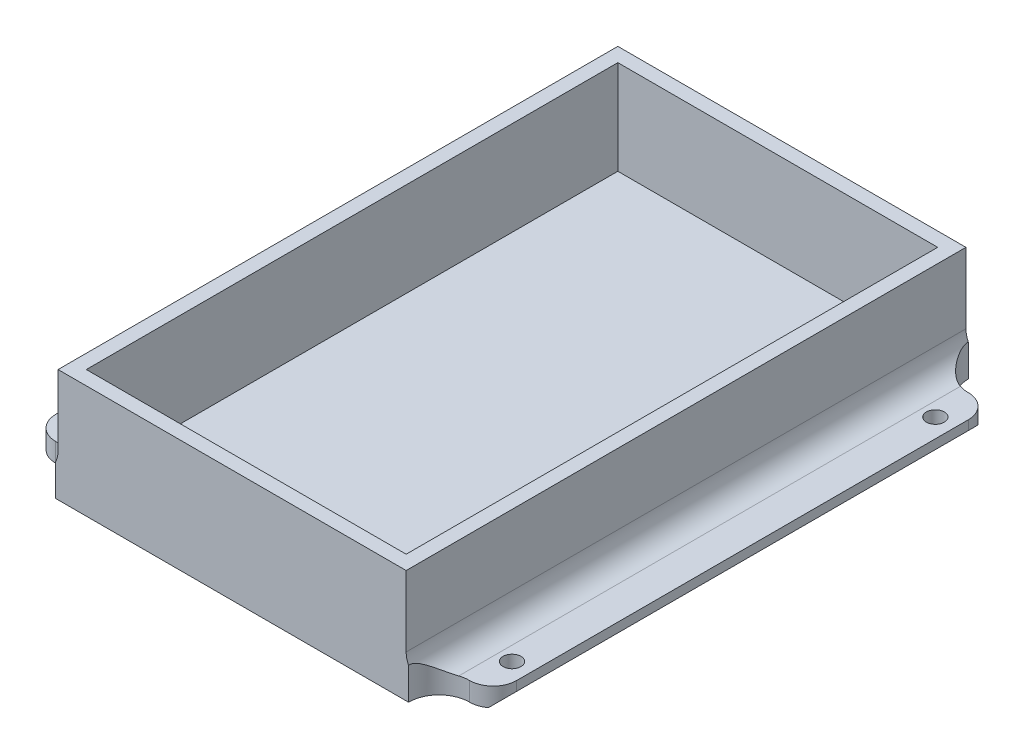
SolidWorks part; units mm, degrees
ref_plane "Спереди" through (0, 0, 0) normal (0, 0, 1) x (1, 0, 0)
ref_plane "Сверху" through (0, 0, 0) normal (0, 1, 0) x (1, 0, 0)
ref_plane "Справа" through (0, 0, 0) normal (1, 0, 0) x (0, 0, -1)
sketch "Эскиз1" plane through (0, 0, 0) normal (0, 1, 0) x (1, 0, 0)
  line L1 (-49, -59.5) -> (49, -59.5)
  line L2 (-49, -59.5) -> (-49, 59.5)
  line L3 (-49, 59.5) -> (49, 59.5)
  line L4 (49, -59.5) -> (49, 59.5)
  line L5 (0, 59.5) -> (0, -59.5) construction
  line L6 (-49, 0) -> (49, 0) construction
  line L7 (-45, -45) -> (45, -45) construction
  line L8 (-45, -45) -> (-45, 45) construction
  line L9 (-45, 45) -> (45, 45) construction
  line L10 (45, -45) -> (45, 45) construction
  line L11 (0, 45) -> (0, -45) construction
  line L12 (-45, 0) -> (45, 0) construction
  circle A0 centre (-45, 45) radius 1.9
  circle A1 centre (45, 45) radius 1.9
  circle A2 centre (45, -45) radius 1.9
  circle A3 centre (-45, -45) radius 1.9
  point P0 (0, 0)
  point P4 (0, 0)
  dimension "D5" = 3.8
  dimension "D1" = 98
  dimension "D2" = 119
  dimension "D3" = 90
  dimension "D4" = 90
extrude "Бобышка-Вытянуть1" add sketch "Эскиз1" along normal blind 4
sketch "Эскиз2" plane through (0, 4, 0) normal (0, 1, 0) x (1, 0, 0)
  line L1 (-34, -56.5) -> (34, -56.5)
  line L2 (-34, -56.5) -> (-34, 56.5)
  line L3 (-34, 56.5) -> (34, 56.5)
  line L4 (34, -56.5) -> (34, 56.5)
  line L5 (0, 56.5) -> (0, -56.5) construction
  line L6 (-34, 0) -> (34, 0) construction
  point P0 (0, 0)
  dimension "D1" = 68
  dimension "D2" = 113
extrude "Вытянуть-Тонкостенный1" add sketch "Эскиз2" along normal blind 20 thin
fillet "Скругление1" radius 5 2 edges at (-37, 4, 0) (37, 4, 0)
chamfer "Фаска1" distance 2 angle 45 2 edges at (49, 0, 0) (-49, 0, 0)
sketch "Эскиз3" plane through (0, 4, 0) normal (0, 1, 0) x (1, 0, 0)
  line L1 (49, 59.5) -> (42, 59.5) construction
  line L2 (49, -59.5) -> (49, 59.5) construction
  line L3 (0, 74.0334) -> (0, 0) construction
  line L4 (0, 0) -> (88.372, 0) construction
  circle A1 centre (44, 59.5) radius 6.5
  circle A4 centre (-44, 59.5) radius 6.5
  circle A5 centre (44, -59.5) radius 6.5
  circle A6 centre (-44, -59.5) radius 6.5
  dimension "D1" = 13
  dimension "D2" = 5
extrude "Вырез-Вытянуть1" cut sketch "Эскиз3" against normal through all both and the other way through all
fillet "Скругление2" radius 5 4 edges at (-49, 3, 55.3467) (49, 3, 55.3467) (-49, 3, -55.3467) (49, 3, -55.3467)
